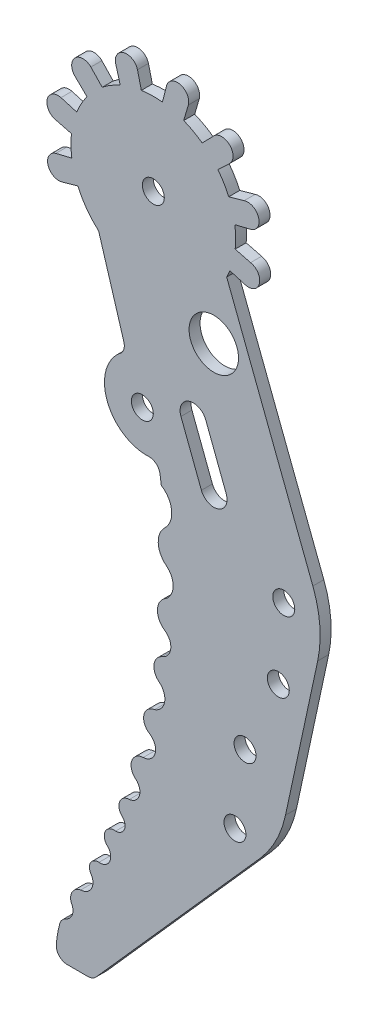
SolidWorks part; units mm, degrees
ref_plane "Front Plane" through (0, 0, 0) normal (0, 0, 1) x (1, 0, 0)
ref_plane "Top Plane" through (0, 0, 0) normal (0, 1, 0) x (1, 0, 0)
ref_plane "Right Plane" through (0, 0, 0) normal (1, 0, 0) x (0, 0, -1)
sketch "Sketch1" plane through (0, 0, 0) normal (0, 0, 1) x (1, 0, 0)
  line L0 (10.1218, 0) -> (2.5, 0) construction
  line L16 (5.147, -5.6126) -> (7.4417, -13.2)
  line L17 (16.8006, -3.4123) -> (24.6469, -23.8519)
  line L18 (25.0875, -29.5388) -> (22.1552, -43.1693)
  line L19 (19.858, -47.7041) -> (4.914, -64.542)
  line L20 (4.1661, -64.8782) -> (2.2859, -64.8782)
  line L21 (2.6676, 0.8279) -> (1.2638, 1.1892)
  line L22 (2.5, 0) -> (1.25, 0) construction
  line L26 (10.1218, 0) -> (-0.1303, -1.4408) construction
  line L27 (2.7011, -1.0876) -> (1.25, -1.4408)
  line L28 (3.2523, -3.0101) -> (1.856, -3.3991)
  line L34 (15.628, -20.9466) -> (13.7664, -16.0577) construction
  line L35 (14.5003, -21.376) -> (12.6387, -16.4871)
  line L36 (16.7556, -20.5172) -> (14.8941, -15.6283)
  line L37 (22, -26.4997) -> (42.7977, -26.4997) construction
  line L38 (17.5548, -46.4997) -> (44.5231, -46.4997) construction
  line L41 (1.25, -4.8178) -> (1.25, -68.9399) construction
  line L42 (3.1515, 2.7685) -> (1.7182, 3.1881)
  line L43 (4.0802, 4.4441) -> (3.0452, 5.4588)
  line L44 (5.4696, 5.8828) -> (4.4381, 6.9628)
  line L45 (7.1117, 6.8695) -> (6.7226, 8.2658)
  line L46 (9.0342, 7.4207) -> (8.681, 8.8718)
  line L47 (10.9497, 7.4542) -> (11.3109, 8.8579)
  line L48 (12.8903, 6.9703) -> (13.3099, 8.4036)
  line L49 (14.5659, 6.0415) -> (15.5806, 7.0766)
  line L50 (16.0045, 4.6522) -> (17.0846, 5.6837)
  line L51 (16.9912, 3.0101) -> (18.3876, 3.3991)
  line L52 (17.5425, 1.0876) -> (18.9936, 1.4408)
  line L53 (17.5759, -0.8279) -> (18.9797, -1.1892)
  line L54 (17.0921, -2.7685) -> (18.5254, -3.1881)
  line L55 (22, -26.4997) -> (21.5, -33.1664) construction
  line L63 (4.239, -4.6522) -> (3.159, -5.6837) [skipped]
  line L64 (5.6777, -6.0415) -> (5.3468, -6.3791) [skipped]
  line L65 (7.3533, -6.9703) -> (6.9337, -8.4036) [skipped]
  line L66 (9.2939, -7.4542) -> (8.9326, -8.8579) [skipped]
  line L67 (11.2093, -7.4207) -> (11.5626, -8.8718) [skipped]
  line L68 (13.5028, -8.2008) -> (13.543, -8.3449) [skipped]
  line L69 (14.774, -5.8828) -> (15.7752, -6.9311) [skipped]
  line L70 (16.1633, -4.4441) -> (17.1984, -5.4588) [skipped]
  arc A13 (7.1115, -14.2685) -> (9.6978, -21.1131) centre (9.5249, -17.2675) ccw
  arc A16 (1.25, -1.4408) -> (1.856, -3.3991) centre (1.5208, -2.43) ccw
  arc A23 (10.7326, -21.97) -> (10.8477, -22.8183) centre (-44.6411, -29.9177) cw
  arc A24 (1.6015, -62) -> (1.2897, -63.791) centre (11.9543, -64.725) ccw
  arc A25 (4.914, -64.542) -> (4.1661, -64.8782) centre (4.1661, -63.8782) cw
  arc A26 (2.2859, -64.8782) -> (1.2897, -63.791) centre (2.2859, -63.8782) cw
  arc A27 (22.1552, -43.1693) -> (19.858, -47.7041) centre (12.3789, -41.0662) cw
  arc A28 (24.6469, -23.8519) -> (25.0875, -29.5388) centre (15.3111, -27.4357) cw
  circle A30 centre (10.1218, 0) radius 1
  circle A31 centre (15.628, -9.2603) radius 2.25
  circle A32 centre (9.1218, -17.5263) radius 0.9981
  arc A33 (14.5003, -21.376) -> (16.7556, -20.5172) centre (15.628, -20.9466) ccw
  arc A34 (14.8941, -15.6283) -> (12.6387, -16.4871) centre (13.7664, -16.0577) ccw
  circle A35 centre (22, -26.4997) radius 1
  circle A36 centre (21.5, -33.1664) radius 1
  circle A37 centre (18.4742, -39.833) radius 1
  circle A38 centre (17.5548, -46.4997) radius 1
  arc A39 (3.5195, -58.3776) -> (4.478, -56.6894) centre (3.4947, -57.2474) ccw
  arc A40 (4.478, -56.6894) -> (5.1728, -55.3731) centre (5.1184, -56.1859) cw
  arc A41 (5.1728, -55.3731) -> (5.9791, -53.7296) centre (5.2695, -54.401) ccw
  arc A42 (5.9791, -53.7296) -> (6.6933, -52.1481) centre (6.5575, -53.0388) cw
  arc A43 (6.6933, -52.1481) -> (7.2971, -50.6981) centre (6.7052, -51.3023) ccw
  arc A44 (7.2971, -50.6981) -> (7.932, -49.0351) centre (7.9512, -49.9951) cw
  arc A45 (7.932, -49.0351) -> (8.5712, -47.1764) centre (7.8216, -47.9579) ccw
  arc A46 (8.5712, -47.1764) -> (9.2023, -45.0931) centre (9.247, -46.2439) cw
  arc A47 (9.2023, -45.0931) -> (9.7684, -42.9183) centre (9.1568, -43.9202) ccw
  arc A48 (9.7684, -42.9183) -> (10.2303, -40.8052) centre (10.39, -41.9471) cw
  arc A49 (10.2303, -40.8052) -> (10.6508, -38.4154) centre (9.7964, -39.497) ccw
  arc A50 (10.6508, -38.4154) -> (10.9372, -36.2787) centre (11.4277, -37.432) cw
  arc A51 (10.9372, -36.2787) -> (11.1453, -34.0756) centre (10.4704, -35.1232) ccw
  arc A52 (11.1453, -34.0756) -> (11.277, -31.5211) centre (12.0035, -32.8392) cw
  arc A53 (11.277, -31.5211) -> (11.2908, -28.902) centre (10.2837, -30.2063) ccw
  arc A54 (11.2908, -28.902) -> (11.1632, -26.0077) centre (12.4931, -27.399) cw
  arc A55 (11.1632, -26.0077) -> (10.8477, -22.8183) centre (9.7776, -24.5344) ccw
  arc A57 (9.6978, -21.1131) -> (10.7326, -21.97) centre (9.7427, -22.112) cw
  arc A58 (7.4417, -13.2) -> (7.1115, -14.2685) centre (6.4845, -13.4895) cw
  arc A59 (3.5195, -58.3776) -> (2.639, -59.7833) centre (3.7042, -59.4719) ccw
  arc A60 (2.639, -59.7833) -> (2.1678, -61.3383) centre (1.7398, -60.3597) cw
  arc A61 (2.1678, -61.3383) -> (1.6015, -62) centre (2.5686, -62.2545) ccw
  arc A70 (16.8006, -3.4123) -> (17.0921, -2.7685) centre (10.1218, 0) ccw
  arc A71 (1.7182, 3.1881) -> (1.2638, 1.1892) centre (1.4581, 2.1961) ccw
  arc A72 (4.4381, 6.9628) -> (3.0452, 5.4588) centre (3.7169, 6.2337) ccw
  arc A73 (8.681, 8.8718) -> (6.7226, 8.2658) centre (7.6918, 8.601) ccw
  arc A74 (13.3099, 8.4036) -> (11.3109, 8.8579) centre (12.3179, 8.6637) ccw
  arc A76 (2.6948, -1.0438) -> (2.7011, -1.0876) centre (10.1218, 0) ccw
  arc A78 (17.0846, 5.6837) -> (15.5806, 7.0766) centre (16.3555, 6.4049) ccw
  arc A79 (18.9936, 1.4408) -> (18.3876, 3.3991) centre (18.7228, 2.43) ccw
  arc A80 (18.5254, -3.1881) -> (18.9797, -1.1892) centre (18.7855, -2.1961) ccw
  arc A81 (3.2523, -3.0101) -> (5.147, -5.6126) centre (10.1218, 0) ccw
  arc A82 (17.5759, -0.8279) -> (17.5425, 1.0876) centre (10.1218, 0) ccw
  arc A83 (16.9912, 3.0101) -> (16.0045, 4.6522) centre (10.1218, 0) ccw
  arc A84 (14.5659, 6.0415) -> (12.8903, 6.9703) centre (10.1218, 0) ccw
  arc A85 (3.159, -5.6837) -> (4.663, -7.0766) centre (3.8881, -6.4049) ccw [skipped]
  arc A86 (6.9337, -8.4036) -> (8.9326, -8.8579) centre (7.9257, -8.6637) ccw [skipped]
  arc A87 (13.2667, -9.3362) -> (13.5427, -8.3369) centre (12.5517, -8.601) ccw [skipped]
  arc A88 (16.7963, -7.2232) -> (17.2528, -5.5095) centre (16.5267, -6.2337) ccw [skipped]
  arc A89 (10.9497, 7.4542) -> (9.0342, 7.4207) centre (10.1218, 0) ccw
  arc A90 (4.0802, 4.4441) -> (3.1515, 2.7685) centre (10.1218, 0) ccw
  arc A91 (7.1117, 6.8695) -> (5.4696, 5.8828) centre (10.1218, 0) ccw
  arc A92 (2.6676, 0.8279) -> (2.7011, -1.0876) centre (10.1218, 0) ccw
  point P59 (1.25, -64.8782)
  point P68 (10.1218, 0)
  point P88 (10.1218, 0)
  point P90 (10.1218, 0)
  point P105 (14.6972, -18.5021)
  point P119 (11.1632, -26.0077)
  point P122 (11.2908, -28.902)
  point P123 (11.277, -31.5211)
  point P124 (11.1453, -34.0756)
  point P125 (10.9372, -36.2787)
  point P126 (10.6508, -38.4154)
  point P127 (10.8477, -22.8183)
  point P128 (10.2303, -40.8052)
  point P129 (9.7684, -42.9183)
  point P130 (9.2023, -45.0931)
  point P131 (8.5712, -47.1764)
  point P132 (7.932, -49.0351)
  point P133 (7.2971, -50.6981)
  point P134 (6.6933, -52.1481)
  point P135 (5.9791, -53.7296)
  point P136 (5.1728, -55.3731)
  point P137 (4.478, -56.6894)
  point P138 (3.5195, -58.3776)
  dimension "D2" = 15
  dimension "D5" = 18.4742
  dimension "D6" = 1
  dimension "D7" = 10
  dimension "D8" = 2
  dimension "D9" = 4.5
  dimension "D10" = 1.9961
  dimension "D12" = 2
  dimension "D15" = 1
  dimension "D16" = 1
  dimension "D3" = 12
  dimension "D4" = 17.5548
  dimension "D11" = 20
  dimension "D13" = 6.6854
  dimension "D14" = 6.6667
  dimension "D17" = 8
  dimension "D18" = 22
  dimension "D19" = 21.5
  dimension "D20" = 26.4997
extrude "Boss-Extrude2" add sketch "Sketch1" along normal blind 1 contours L21 A92 A76 L27 A16 L28 A81 L16 A58 A13 A57 A23 A55 A54 A53 A52 A51 A50 A49 A48 A47 A46 A45 A44 A43 A42 A41 A40 A39 A59 A60 A61 A24 A26 L20 A25 L19 A27 L18 A28 L17 A70 L54 A80 L53 A82 L52 A79 L51 A83 L50
